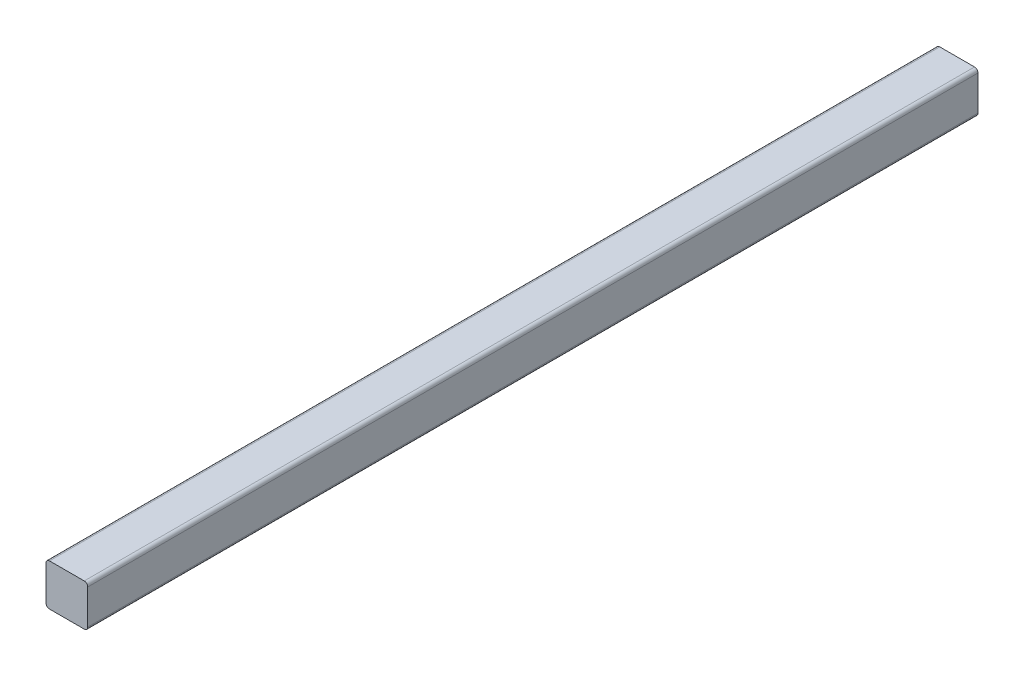
SolidWorks part; units mm, degrees
ref_plane "Front Plane" through (0, 0, 0) normal (0, 0, 1) x (1, 0, 0)
ref_plane "Top Plane" through (0, 0, 0) normal (0, 1, 0) x (1, 0, 0)
ref_plane "Right Plane" through (0, 0, 0) normal (1, 0, 0) x (0, 0, -1)
sketch "Sketch1" plane through (0, 0, 0) normal (0, 0, 1) x (1, 0, 0)
  line L1 (-19.05, -19.05) -> (19.05, -19.05)
  line L2 (-19.05, -19.05) -> (-19.05, 19.05)
  line L3 (-19.05, 19.05) -> (19.05, 19.05)
  line L4 (19.05, -19.05) -> (19.05, 19.05)
  line L5 (-19.05, -19.05) -> (19.05, 19.05) construction
  line L6 (-19.05, 19.05) -> (19.05, -19.05) construction
  point P0 (0, 0)
  dimension "D1" = 38.1
  dimension "D2" = 38.1
extrude "Boss-Extrude1" add sketch "Sketch1" along normal blind 812.8
fillet "Fillet1" radius 3.175 4 edges at (-19.05, 19.05, 406.4) (-19.05, -19.05, 406.4) (19.05, -19.05, 406.4) (19.05, 19.05, 406.4)
